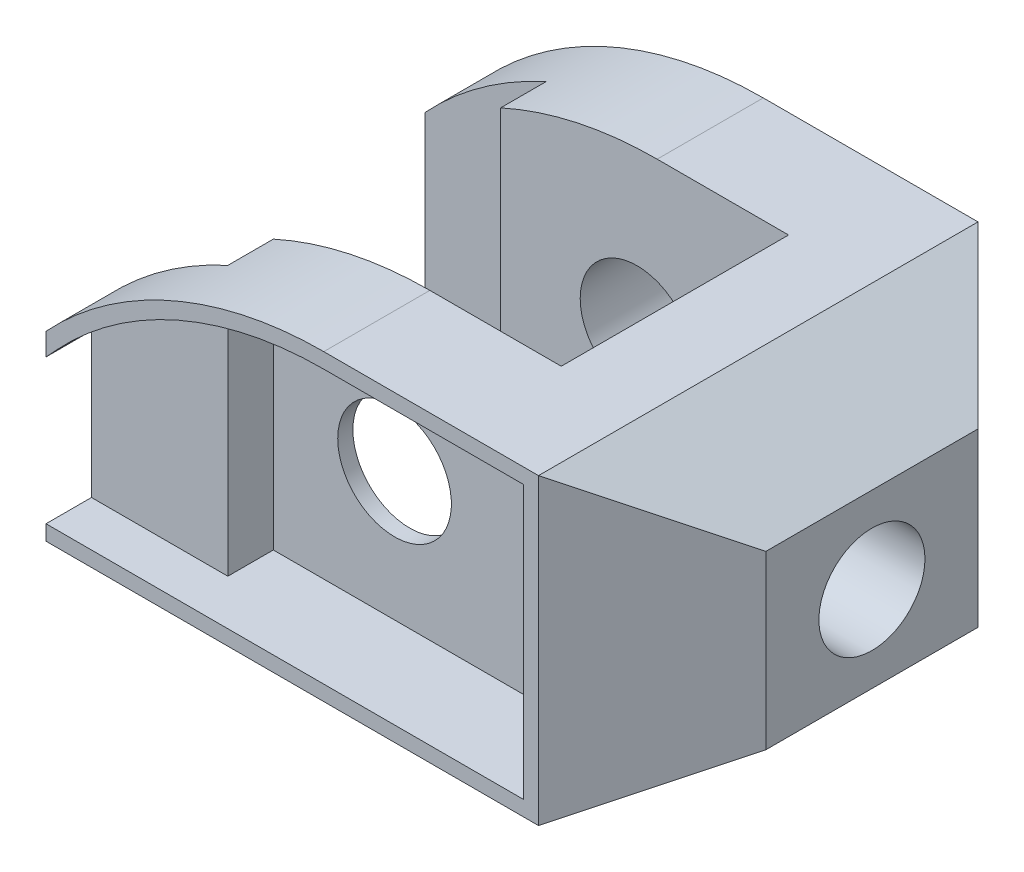
SolidWorks part; units mm, degrees
material "1060 Alloy"
ref_plane "Front Plane" through (0, 0, 0) normal (0, 0, 1) x (1, 0, 0)
ref_plane "Top Plane" through (0, 0, 0) normal (0, 1, 0) x (1, 0, 0)
ref_plane "Right Plane" through (0, 0, 0) normal (1, 0, 0) x (0, 0, -1)
sketch "Sketch1" plane through (0, 0, 0) normal (0, 0, 1) x (1, 0, 0)
  line L0 (0, 0) -> (65, 0)
  line L1 (65, 0) -> (80, 8.6603)
  line L2 (80, 8.6603) -> (80, 31.3397)
  line L3 (80, 31.3397) -> (65, 40)
  line L4 (65, 40) -> (36.6606, 40)
  line L5 (0, 0) -> (0, 24)
  arc A0 (0, 24) -> (36.6606, 40) centre (36.6606, -10) cw
  circle A1 centre (34, 19) radius 7.5
  dimension "D8" = 50
  dimension "D11" = 15
  dimension "D1" = 30
  dimension "D2" = 30
  dimension "D3" = 40
  dimension "D4" = 65
  dimension "D5" = 15
  dimension "D6" = 15
  dimension "D7" = 24
  dimension "D9" = 19
  dimension "D10" = 31
extrude "Boss-Extrude1" add sketch "Sketch1" along normal blind 58
sketch "Sketch2" plane through (0, 0, 0) normal (0, -1, 0) x (1, 0, 0)
  line L0 (65, 58) -> (65, 0) construction
  line L1 (0, 0) -> (65, 0) construction
  line L2 (65, 0) -> (80, 0) construction
  line L3 (80, 58) -> (80, 0) construction
  line L4 (65, 58) -> (80, 58) construction
  line L5 (0, 58) -> (65, 58) construction
  line L6 (65, 58) -> (65, 0)
  line L7 (0, 0) -> (65, 0)
  line L8 (65, 0) -> (80, 0)
  line L9 (80, 58) -> (80, 0)
  line L10 (65, 58) -> (80, 58)
  line L11 (0, 58) -> (65, 58)
  line L12 (65, 0) -> (80, 15)
  line L13 (80, 15) -> (80, 43)
  line L14 (80, 43) -> (65, 58)
  line L15 (80, 43) -> (80, 58)
  line L16 (80, 58) -> (65, 58)
  line L17 (65, 58) -> (80, 43)
  line L18 (80, 15) -> (80, 0)
  line L19 (80, 0) -> (65, 0)
  line L20 (65, 0) -> (80, 15)
  dimension "D1" = 45
  dimension "D2" = 45
extrude "Cut-Extrude1" cut sketch "Sketch2" against normal through all contours L14 L9 L10 | L12 L8 L9
sketch "Sketch3" plane through (80, 0, 0) normal (1, 0, 0) x (0, 0, -1)
  line L0 (-58, 0) -> (0, 0) construction
  line L1 (-58, 40) -> (-58, 0) construction
  circle A0 centre (-29, 20) radius 7
  point P6 (-28.6083, 19.3285)
  dimension "D3" = 14
  dimension "D1" = 20
  dimension "D2" = 29
extrude "Cut-Extrude2" cut sketch "Sketch3" against normal through all
sketch "Sketch5" plane through (0, 40, 0) normal (0, 1, 0) x (1, 0, 0)
  line L0 (0, 0) -> (0, -8)
  line L1 (0, -23.2554) -> (0, 0) construction
  line L2 (0, -8) -> (16, -8)
  line L3 (16, -8) -> (16, -14)
  line L4 (16, -14) -> (36.6606, -14)
  line L5 (36.6606, -58) -> (36.6606, 0) construction
  line L6 (65, -29) -> (-19.9756, -29) construction
  line L7 (65, -58) -> (65, 0) construction
  line L8 (36.6606, -14) -> (54, -14)
  line L9 (54, -14) -> (54, -44)
  line L10 (36.6606, -44) -> (54, -44)
  line L11 (16, -44) -> (36.6606, -44)
  line L12 (16, -50) -> (16, -44)
  line L13 (0, -50) -> (16, -50)
  line L14 (0, -58) -> (0, -50)
  line L15 (0, -8) -> (0, -50)
  point P17 (54, -29)
  line M9 (36.6606, 0) -> (36.6606, -58)
  dimension "D1" = 8
  dimension "D2" = 6
  dimension "D3" = 16
  dimension "D4" = 11
extrude "Cut-Extrude3" cut sketch "Sketch5" against normal through all contours L6 L4 L3 L2 L15 M9 | L6 L9 L8 M9 | L9 L6 L10 M9 | L6 L15 L13 L12 L11 M9
sketch "Sketch6" plane through (0, 0, 58) normal (0, 0, 1) x (1, 0, 0)
  line L0 (0, 2) -> (63, 2)
  line L1 (63, 2) -> (63, 38)
  line L2 (63, 38) -> (36.6606, 38)
  line L3 (1.4664, 22.64) -> (0, 21.0588)
  line L4 (65, 0) -> (65, 40)
  line L5 (65, 40) -> (36.6606, 40)
  line L6 (0, 24) -> (0, 0)
  line L7 (0, 0) -> (65, 0)
  line L8 (65, 0) -> (65, 40)
  line L9 (65, 40) -> (36.6606, 40)
  line L10 (0, 24) -> (0, 0)
  line L11 (0, 0) -> (65, 0)
  line L12 (18, 34.2242) -> (18, 2)
  arc A0 (36.6606, 38) -> (1.4664, 22.64) centre (36.6606, -10) ccw
  arc A1 (36.6606, 40) -> (0, 24) centre (36.6606, -10) ccw
  arc A2 (36.6606, 40) -> (0, 24) centre (36.6606, -10) ccw
  circle M7 centre (34, 19) radius 7.5
  dimension "D3" = 18
  dimension "D1" = 0
  dimension "D2" = 2
extrude "Cut-Extrude4" cut sketch "Sketch6" against normal blind 12 contours L2 A0 L12 L0 L1 M7
sketch "Sketch7" plane through (0, 0, 58) normal (0, 0, 1) x (1, 0, 0)
  line L0 (18, 34.2242) -> (18, 2)
  line L1 (18, 2) -> (0, 2)
  line L2 (0, 24) -> (0, 0) construction
  line L3 (1.4664, 22.64) -> (0, 21.0588)
  line L4 (0, 21.0588) -> (0, 2)
  arc A0 (36.6606, 40) -> (0, 24) centre (36.6606, -10) ccw construction
  arc A1 (36.6606, 40) -> (0, 24) centre (36.6606, -10) ccw
  arc A2 (36.6606, 38) -> (1.4664, 22.64) centre (36.6606, -10) ccw
  line M5 (18, 2) -> (18, 34.2242)
  line M9 (0, 24) -> (0, 0)
  dimension "D1" = 2
extrude "Cut-Extrude5" cut sketch "Sketch7" against normal blind 6 contours A2 L3 L1 M5 M9
equation "\"a\"= 58mm"
equation "\"b\"= 40mm"
equation "\"c\"= 65mm"
